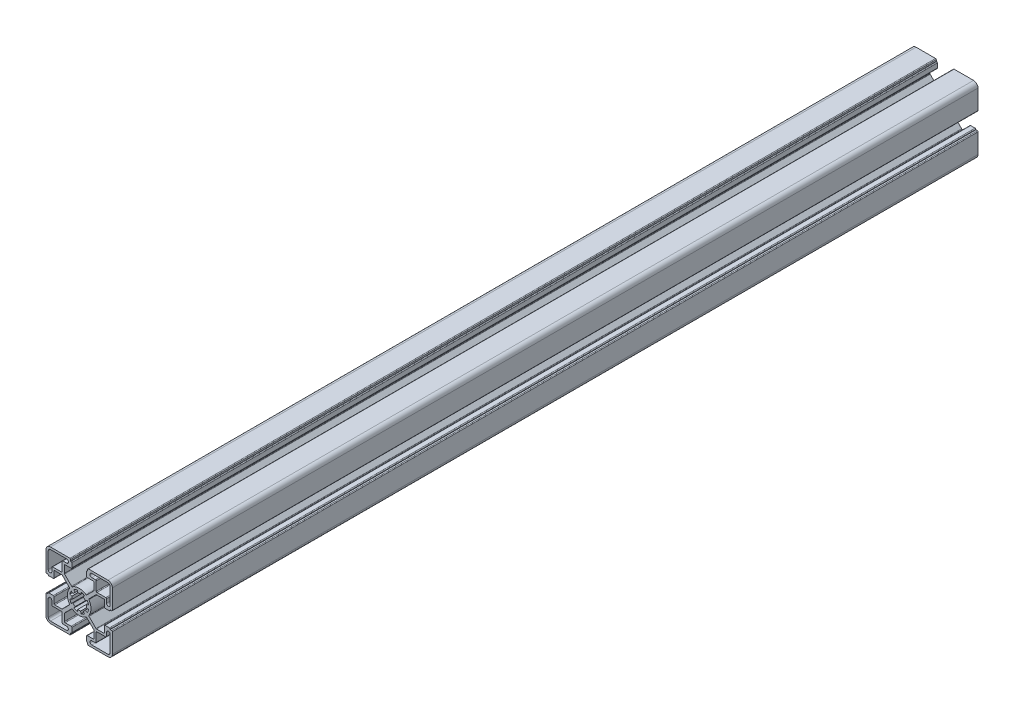
SolidWorks part; units mm, degrees
material "6063-O"
ref_plane "Front Plane" through (0, 0, 0) normal (0, 0, 1) x (1, 0, 0)
ref_plane "Top Plane" through (0, 0, 0) normal (0, 1, 0) x (1, 0, 0)
ref_plane "Right Plane" through (0, 0, 0) normal (1, 0, 0) x (0, 0, -1)
sketch "Sketch1" plane through (0, 0, 0) normal (0, 0, 1) x (1, 0, 0)
  line L0 (0, 22.5) -> (0, -22.5) construction
  line L1 (22.5, 0) -> (-22.5, 0) construction
  line L2 (-5.8, 22.5) -> (5.8, 22.5) construction
  line L3 (-5, 21) -> (5, 21) construction
  line L4 (-10.05, 10.05) -> (10.05, 10.05) construction
  line L5 (0, 0) -> (-10.05, 10.05) construction
  circle A0 centre (0, 0) radius 5 construction
  point P4 (0, 0)
  point P8 (0, 0)
  point P10 (0, 8)
  point P14 (0, 22.5)
  point P17 (0, 21)
  point P19 (0, 10.05)
sketch "Sketch2" plane through (0, 0, 0) normal (1, 0, 0) x (0, 0, -1)
  line L0 (152.4, 0) -> (-152.4, 0) construction
  point P4 (0, 0)
  dimension "D1" = 304.8
sketch "Sketch3" plane through (0, 0, 0) normal (0, 0, 1) x (1, 0, 0)
  line L5 (-21, 8.5375) -> (-21, 19.5)
  line L9 (0, 0) -> (-22.5, 22.5) construction
  line L10 (-11.55, -10.05) -> (-6.3569, -4.8569)
  line L11 (-19.5, 21) -> (-8.5375, 21)
  line L38 (-5.8, 22.5) -> (-5.8, 21)
  line L46 (-5.8, 21) -> (-5, 21)
  line L62 (-5, 21) -> (-5, 17.025)
  line L74 (-5, 17.025) -> (-10.05, 17.025)
  line L76 (-10.05, 17.025) -> (-10.05, 11.55)
  line L77 (-10.05, 11.55) -> (-4.8569, 6.3569)
  line L78 (-18.525, 8.5375) -> (-18.525, 11.55)
  line L79 (-10.05, 17.025) -> (-10.05, 22.5) construction
  line L80 (0, 22.5) -> (0, -22.5) construction
  line L81 (-5.8, 22.5) -> (5.8, 22.5) construction
  line L82 (10.05, 11.55) -> (4.8569, 6.3569)
  line L83 (10.05, 17.025) -> (10.05, 11.55)
  line L84 (5, 17.025) -> (10.05, 17.025)
  line L85 (5, 21) -> (5, 17.025)
  line L86 (5.8, 21) -> (5, 21)
  line L87 (5.8, 22.5) -> (5.8, 21)
  line L88 (-22.5, -5.8) -> (-21, -5.8)
  line L89 (-21, -5.8) -> (-21, -5)
  line L90 (-21, -5) -> (-17.025, -5)
  line L91 (-17.025, -5) -> (-17.025, -10.05)
  line L92 (-17.025, -10.05) -> (-11.55, -10.05)
  line L93 (-11.55, -10.05) -> (-6.3569, -4.8569)
  line L94 (-11.55, 10.05) -> (-6.3569, 4.8569)
  line L95 (-17.025, 10.05) -> (-11.55, 10.05)
  line L96 (-17.025, 5) -> (-17.025, 10.05)
  line L97 (-21, 5) -> (-17.025, 5)
  line L98 (-21, 5.8) -> (-21, 5)
  line L99 (-22.5, 5.8) -> (-21, 5.8)
  line L100 (-22.5, 5.8) -> (-22.5, 19.5)
  line L101 (-19.5, 22.5) -> (-5.8, 22.5)
  line L102 (-18.525, 11.55) -> (-11.55, 11.55)
  line L103 (-8.5375, 18.525) -> (-11.55, 18.525)
  line L104 (-11.55, 18.525) -> (-11.55, 11.55)
  line L108 (5.8, -22.5) -> (5.8, -21)
  line L113 (5.8, -21) -> (5, -21)
  line L117 (5.8, 22.5) -> (19.5, 22.5)
  line L118 (22.5, 19.5) -> (22.5, 5.8)
  line L119 (19.5, -22.5) -> (5.8, -22.5)
  line L120 (0, 0) -> (22.5, 0) construction
  line L121 (-22.5, -19.5) -> (-22.5, -5.8)
  line L136 (5, -21) -> (5, -17.025)
  line L137 (5, -17.025) -> (10.05, -17.025)
  line L138 (10.05, -17.025) -> (10.05, -11.55)
  line L139 (10.05, -11.55) -> (4.8569, -6.3569)
  line L140 (-10.05, -11.55) -> (-4.8569, -6.3569)
  line L141 (-10.05, -17.025) -> (-10.05, -11.55)
  line L142 (-5, -17.025) -> (-10.05, -17.025)
  line L143 (-5, -21) -> (-5, -17.025)
  line L144 (-5.8, -21) -> (-5, -21)
  line L145 (-5.8, -22.5) -> (-5.8, -21)
  line L146 (-5.8, -22.5) -> (-19.5, -22.5)
  line L147 (22.5, 5.8) -> (21, 5.8)
  line L148 (21, 5.8) -> (21, 5)
  line L149 (21, 5) -> (17.025, 5)
  line L150 (17.025, 5) -> (17.025, 10.05)
  line L151 (17.025, 10.05) -> (11.55, 10.05)
  line L152 (11.55, 10.05) -> (6.3569, 4.8569)
  line L153 (11.55, -10.05) -> (6.3569, -4.8569)
  line L154 (17.025, -10.05) -> (11.55, -10.05)
  line L155 (17.025, -5) -> (17.025, -10.05)
  line L156 (21, -5) -> (17.025, -5)
  line L157 (21, -5.8) -> (21, -5)
  line L158 (22.5, -5.8) -> (21, -5.8)
  line L159 (11.55, -10.05) -> (6.3569, -4.8569)
  line L160 (22.5, -5.8) -> (22.5, -19.5)
  line L161 (8.5375, 21) -> (19.5, 21)
  line L162 (21, 19.5) -> (21, 8.5375)
  line L163 (8.5375, 18.525) -> (11.55, 18.525)
  line L164 (11.55, 18.525) -> (11.55, 11.55)
  line L165 (18.525, 8.5375) -> (18.525, 11.55)
  line L166 (18.525, 11.55) -> (11.55, 11.55)
  line L167 (21, -8.5375) -> (21, -19.5)
  line L168 (19.5, -21) -> (8.5375, -21)
  line L169 (18.525, -8.5375) -> (18.525, -11.55)
  line L170 (18.525, -11.55) -> (11.55, -11.55)
  line L171 (8.5375, -18.525) -> (11.55, -18.525)
  line L172 (11.55, -18.525) -> (11.55, -11.55)
  line L173 (-8.5375, -21) -> (-19.5, -21)
  line L174 (-21, -19.5) -> (-21, -8.5375)
  line L175 (-8.5375, -18.525) -> (-11.55, -18.525)
  line L176 (-11.55, -18.525) -> (-11.55, -11.55)
  line L177 (-18.525, -8.5375) -> (-18.525, -11.55)
  line L178 (-18.525, -11.55) -> (-11.55, -11.55)
  line L179 (0, 0) -> (-11.55, 11.55) construction
  line L180 (0, 0) -> (11.55, 11.55) construction
  arc A2 (-21, 19.5) -> (-19.5, 21) centre (-19.5, 19.5) cw
  arc A73 (-4.8569, 6.3569) -> (4.8569, 6.3569) centre (0, 0) cw
  arc A74 (-6.3569, 4.8569) -> (-6.3569, -4.8569) centre (0, 0) ccw
  arc A75 (-19.5, 22.5) -> (-22.5, 19.5) centre (-19.5, 19.5) ccw
  arc A76 (-21, 8.5375) -> (-18.525, 8.5375) centre (-19.7625, 8.5375) ccw
  arc A77 (-8.5375, 21) -> (-8.5375, 18.525) centre (-8.5375, 19.7625) cw
  arc A80 (19.5, 22.5) -> (22.5, 19.5) centre (19.5, 19.5) cw
  arc A81 (22.5, -19.5) -> (19.5, -22.5) centre (19.5, -19.5) cw
  arc A82 (-19.5, -22.5) -> (-22.5, -19.5) centre (-19.5, -19.5) cw
  circle A88 centre (0, 0) radius 5 construction
  circle A89 centre (0, 0) radius 5
  arc A90 (-4.8569, -6.3569) -> (4.8569, -6.3569) centre (0, 0) ccw
  arc A91 (19.5, 21) -> (21, 19.5) centre (19.5, 19.5) cw
  arc A92 (6.3569, 4.8569) -> (6.3569, -4.8569) centre (0, 0) cw
  arc A93 (8.5375, 21) -> (8.5375, 18.525) centre (8.5375, 19.7625) ccw
  arc A94 (21, 8.5375) -> (18.525, 8.5375) centre (19.7625, 8.5375) cw
  arc A95 (21, -19.5) -> (19.5, -21) centre (19.5, -19.5) cw
  arc A96 (21, -8.5375) -> (18.525, -8.5375) centre (19.7625, -8.5375) ccw
  arc A97 (8.5375, -21) -> (8.5375, -18.525) centre (8.5375, -19.7625) cw
  arc A98 (-19.5, -21) -> (-21, -19.5) centre (-19.5, -19.5) cw
  arc A99 (-8.5375, -21) -> (-8.5375, -18.525) centre (-8.5375, -19.7625) ccw
  arc A100 (-21, -8.5375) -> (-18.525, -8.5375) centre (-19.7625, -8.5375) cw
  point P54 (-14.2875, 10.05)
  dimension "D2" = 3
  dimension "D3" = 1.5
  dimension "D4" = 1.5
  dimension "D5" = 1.5
  dimension "D6" = 90
  dimension "D1" = 4
extrude "Boss-Extrude1" add sketch "Sketch3" along normal up to vertex (152.4 mm away) and the other way up to vertex (152.4 mm away) contours A92 L152 L151 L150 L149 L148 L147 L118 A80 L117 L87 L86 L85 L84 L83 L82 A73 L77 L76 L74 L62 L46 L38 L101 A75 L100 L99 L98 L97 L96 L95 L94 A74 L10 L92 L91 L90 L89 L88 L121 A82 L146 L145 L144 L143 L142 L141 L140 A90 L139 L138 up to point (0, 0, 152.4) other way up to point (0, 0, -152.4)
fillet "Fillet1" radius 0.5 58 edges at (5, 21, 0) (5.8, 22.5, 0) (-5.8, 22.5, 0) (-5, 21, 0) (-10.05, 17.025, 0) (-5, 17.025, 0) (5, 17.025, 0) (-22.5, -5.8, 0) (-21, -5, 0) (-17.025, -5, 0) (-17.025, -10.05, 0) (-11.55, -10.05, 0) (-6.3569, -4.8569, 0) (-6.3569, 4.8569, 0) (-11.55, 10.05, 0) (-17.025, 10.05, 0) (-17.025, 5, 0) (-22.5, 5.8, 0) (-21, 5, 0) (-18.525, 11.55, 0) (-11.55, 11.55, 0) (-11.55, 18.525, 0) (4.8569, 6.3569, 0) (-4.8569, 6.3569, 0) (-10.05, 11.55, 0) (10.05, 17.025, 0) (10.05, 11.55, 0) (22.5, -5.8, 0) (21, -5, 0) (17.025, -5, 0) (17.025, -10.05, 0) (6.3569, 4.8569, 0) (11.55, 10.05, 0) (22.5, 5.8, 0) (21, 5, 0) (17.025, 5, 0) (4.8569, -6.3569, 0) (11.55, -11.55, 0) (-11.55, -11.55, 0) (18.525, -11.55, 0) (11.55, -18.525, 0) (10.05, -17.025, 0) (5, -17.025, 0) (5, -21, 0) (5.8, -22.5, 0) (-5.8, -22.5, 0) (-5, -21, 0) (-5, -17.025, 0) (-10.05, -17.025, 0) (-11.55, -18.525, 0) (11.55, 18.525, 0) (18.525, 11.55, 0) (11.55, 11.55, 0) (11.55, -10.05, 0) (6.3569, -4.8569, 0) (-4.8569, -6.3569, 0) (10.05, -11.55, 0) (-10.05, -11.55, 0)
sketch "Sketch4" plane through (0, 0, 152.4) normal (0, 0, 1) x (1, 0, 0)
  line L0 (-1.2681, 6.3751) -> (-0.9755, 4.9039)
  line L1 (0, 0) -> (0, 8) construction
  line L2 (-3.6112, 5.4046) -> (-2.7779, 4.1573)
  line L3 (1.2681, 6.3751) -> (0.9755, 4.9039)
  line L4 (3.6112, 5.4046) -> (2.7779, 4.1573)
  line L5 (5.4046, 3.6112) -> (4.1573, 2.7779)
  line L6 (6.3751, 1.2681) -> (4.9039, 0.9755)
  line L7 (6.3751, -1.2681) -> (4.9039, -0.9755)
  line L8 (5.4046, -3.6112) -> (4.1573, -2.7779)
  line L9 (3.6112, -5.4046) -> (2.7779, -4.1573)
  line L10 (1.2681, -6.3751) -> (0.9755, -4.9039)
  line L11 (-1.2681, -6.3751) -> (-0.9755, -4.9039)
  line L12 (-3.6112, -5.4046) -> (-2.7779, -4.1573)
  line L13 (-5.4046, -3.6112) -> (-4.1573, -2.7779)
  line L14 (-6.3751, -1.2681) -> (-4.9039, -0.9755)
  line L15 (-6.3751, 1.2681) -> (-4.9039, 0.9755)
  line L16 (-5.4046, 3.6112) -> (-4.1573, 2.7779)
  line L17 (0, 0) -> (-0.9755, 4.9039) construction
  line L18 (0, 0) -> (2.7779, 4.1573) construction
  arc A0 (-1.2681, 6.3751) -> (-3.6112, 5.4046) centre (0, 0) ccw
  circle A1 centre (0, 0) radius 5 construction
  arc A2 (-0.9755, 4.9039) -> (-2.7779, 4.1573) centre (0, 0) ccw
  arc A4 (2.7779, 4.1573) -> (0.9755, 4.9039) centre (0, 0) ccw
  arc A5 (3.6112, 5.4046) -> (1.2681, 6.3751) centre (0, 0) ccw
  arc A6 (4.9039, 0.9755) -> (4.1573, 2.7779) centre (0, 0) ccw
  arc A7 (6.3751, 1.2681) -> (5.4046, 3.6112) centre (0, 0) ccw
  arc A8 (4.1573, -2.7779) -> (4.9039, -0.9755) centre (0, 0) ccw
  arc A9 (5.4046, -3.6112) -> (6.3751, -1.2681) centre (0, 0) ccw
  arc A10 (0.9755, -4.9039) -> (2.7779, -4.1573) centre (0, 0) ccw
  arc A11 (1.2681, -6.3751) -> (3.6112, -5.4046) centre (0, 0) ccw
  arc A12 (-2.7779, -4.1573) -> (-0.9755, -4.9039) centre (0, 0) ccw
  arc A13 (-3.6112, -5.4046) -> (-1.2681, -6.3751) centre (0, 0) ccw
  arc A14 (-4.9039, -0.9755) -> (-4.1573, -2.7779) centre (0, 0) ccw
  arc A15 (-6.3751, -1.2681) -> (-5.4046, -3.6112) centre (0, 0) ccw
  arc A16 (-4.1573, 2.7779) -> (-4.9039, 0.9755) centre (0, 0) ccw
  arc A17 (-5.4046, 3.6112) -> (-6.3751, 1.2681) centre (0, 0) ccw
  dimension "D1" = 1.5
  dimension "D2" = 22.5
  dimension "D5" = 45
  dimension "D4" = 8
extrude "Cut-Extrude1" cut sketch "Sketch4" against normal through all
sketch "Sketch6" plane through (0, 0, 152.4) normal (0, 0, 1) x (1, 0, 0)
  line L6 (-11.55, -18.025) -> (-11.55, -12.05)
  line L7 (-8.5375, -18.525) -> (-11.05, -18.525)
  line L8 (-19.5, -21) -> (-8.5375, -21)
  line L9 (-21, -8.5375) -> (-21, -19.5)
  line L10 (-18.525, -11.55) -> (-18.525, -8.5375)
  line L11 (-12.05, -11.55) -> (-18.525, -11.55)
  line L12 (-11.55, -18.025) -> (-11.55, -12.05)
  line L13 (-8.5375, -18.525) -> (-11.05, -18.525)
  line L14 (-19.5, -21) -> (-8.5375, -21)
  line L15 (-21, -8.5375) -> (-21, -19.5)
  line L16 (-0.9755, 4.9039) -> (-1.2681, 6.3751)
  line L17 (1.2681, 6.3751) -> (0.9755, 4.9039)
  line L18 (2.7779, 4.1573) -> (3.6112, 5.4046)
  line L19 (5.4046, 3.6112) -> (4.1573, 2.7779)
  line L20 (4.9039, 0.9755) -> (6.3751, 1.2681)
  line L21 (6.3751, -1.2681) -> (4.9039, -0.9755)
  line L22 (4.1573, -2.7779) -> (5.4046, -3.6112)
  line L23 (3.6112, -5.4046) -> (2.7779, -4.1573)
  line L24 (0.9755, -4.9039) -> (1.2681, -6.3751)
  line L25 (-1.2681, -6.3751) -> (-0.9755, -4.9039)
  line L26 (-2.7779, -4.1573) -> (-3.6112, -5.4046)
  line L27 (-5.4046, -3.6112) -> (-4.1573, -2.7779)
  line L28 (-4.9039, -0.9755) -> (-6.3751, -1.2681)
  line L29 (-6.3751, 1.2681) -> (-4.9039, 0.9755)
  line L30 (-4.1573, 2.7779) -> (-5.4046, 3.6112)
  line L31 (-3.6112, 5.4046) -> (-2.7779, 4.1573)
  line L32 (-0.9755, 4.9039) -> (-1.2681, 6.3751)
  line L33 (1.2681, 6.3751) -> (0.9755, 4.9039)
  line L34 (2.7779, 4.1573) -> (3.6112, 5.4046)
  line L35 (5.4046, 3.6112) -> (4.1573, 2.7779)
  line L36 (4.9039, 0.9755) -> (6.3751, 1.2681)
  line L37 (6.3751, -1.2681) -> (4.9039, -0.9755)
  line L38 (4.1573, -2.7779) -> (5.4046, -3.6112)
  line L39 (3.6112, -5.4046) -> (2.7779, -4.1573)
  line L40 (0.9755, -4.9039) -> (1.2681, -6.3751)
  line L41 (-1.2681, -6.3751) -> (-0.9755, -4.9039)
  line L42 (-2.7779, -4.1573) -> (-3.6112, -5.4046)
  line L43 (-5.4046, -3.6112) -> (-4.1573, -2.7779)
  line L44 (-4.9039, -0.9755) -> (-6.3751, -1.2681)
  line L45 (-6.3751, 1.2681) -> (-4.9039, 0.9755)
  line L46 (-4.1573, 2.7779) -> (-5.4046, 3.6112)
  line L47 (-3.6112, 5.4046) -> (-2.7779, 4.1573)
  line L48 (-18.525, -11.55) -> (-18.525, -8.5375)
  line L49 (-12.05, -11.55) -> (-18.525, -11.55)
  line L50 (18.025, -11.55) -> (12.05, -11.55)
  line L51 (18.525, -8.5375) -> (18.525, -11.05)
  line L52 (21, -19.5) -> (21, -8.5375)
  line L53 (8.5375, -21) -> (19.5, -21)
  line L54 (11.05, -18.525) -> (8.5375, -18.525)
  line L55 (11.55, -12.05) -> (11.55, -18.025)
  line L56 (22.5, -19.5) -> (22.5, -6.3)
  line L57 (22, -5.8) -> (21, -5.8)
  line L58 (21, -5.8) -> (21, -5.5)
  line L59 (20.5, -5) -> (17.525, -5)
  line L60 (17.025, -5.5) -> (17.025, -9.55)
  line L61 (16.525, -10.05) -> (11.7571, -10.05)
  line L62 (11.4036, -9.9036) -> (6.6582, -5.1582)
  line L63 (6.6582, 5.1582) -> (11.4036, 9.9036)
  line L64 (11.7571, 10.05) -> (17.025, 10.05)
  line L65 (17.025, 10.05) -> (17.025, 5.5)
  line L66 (17.525, 5) -> (20.5, 5)
  line L67 (21, 5.5) -> (21, 5.8)
  line L68 (21, 5.8) -> (22, 5.8)
  line L69 (22.5, 6.3) -> (22.5, 19.5)
  line L70 (19.5, 22.5) -> (6.3, 22.5)
  line L71 (5.8, 22) -> (5.8, 21)
  line L72 (5.8, 21) -> (5.5, 21)
  line L73 (5, 20.5) -> (5, 17.525)
  line L74 (5.5, 17.025) -> (9.55, 17.025)
  line L75 (10.05, 16.525) -> (10.05, 11.7571)
  line L76 (9.9036, 11.4036) -> (5.1582, 6.6582)
  line L77 (-5.1582, 6.6582) -> (-9.9036, 11.4036)
  line L78 (-10.05, 11.7571) -> (-10.05, 16.525)
  line L79 (-9.55, 17.025) -> (-5.5, 17.025)
  line L80 (-5, 17.525) -> (-5, 20.5)
  line L81 (-5.5, 21) -> (-5.8, 21)
  line L82 (-5.8, 21) -> (-5.8, 22)
  line L83 (-6.3, 22.5) -> (-19.5, 22.5)
  line L84 (-22.5, 19.5) -> (-22.5, 6.3)
  line L85 (-22, 5.8) -> (-21, 5.8)
  line L86 (-21, 5.8) -> (-21, 5.5)
  line L87 (-20.5, 5) -> (-17.525, 5)
  line L88 (-17.025, 5.5) -> (-17.025, 9.55)
  line L89 (-16.525, 10.05) -> (-11.7571, 10.05)
  line L90 (-11.4036, 9.9036) -> (-6.6582, 5.1582)
  line L91 (-6.6582, -5.1582) -> (-11.4036, -9.9036)
  line L92 (-11.7571, -10.05) -> (-16.525, -10.05)
  line L93 (-17.025, -9.55) -> (-17.025, -5.5)
  line L94 (-17.525, -5) -> (-20.5, -5)
  line L95 (-21, -5.5) -> (-21, -5.8)
  line L96 (-21, -5.8) -> (-22, -5.8)
  line L97 (-22.5, -6.3) -> (-22.5, -19.5)
  line L98 (-19.5, -22.5) -> (-6.3, -22.5)
  line L99 (-5.8, -22) -> (-5.8, -21)
  line L100 (-5.8, -21) -> (-5.5, -21)
  line L101 (-5, -20.5) -> (-5, -17.525)
  line L102 (-5.5, -17.025) -> (-9.55, -17.025)
  line L103 (-10.05, -16.525) -> (-10.05, -11.7571)
  line L104 (-9.9036, -11.4036) -> (-5.1582, -6.6582)
  line L105 (5.1582, -6.6582) -> (9.9036, -11.4036)
  line L106 (10.05, -11.7571) -> (10.05, -16.525)
  line L107 (9.55, -17.025) -> (5.5, -17.025)
  line L108 (5, -17.525) -> (5, -20.5)
  line L109 (5.5, -21) -> (5.8, -21)
  line L110 (5.8, -21) -> (5.8, -22)
  line L111 (6.3, -22.5) -> (19.5, -22.5)
  line L112 (22.5, -19.5) -> (22.5, -6.3)
  line L113 (22, -5.8) -> (21, -5.8)
  line L114 (21, -5.8) -> (21, -5.5)
  line L115 (20.5, -5) -> (17.525, -5)
  line L116 (17.025, -5.5) -> (17.025, -9.55)
  line L117 (16.525, -10.05) -> (11.7571, -10.05)
  line L118 (11.4036, -9.9036) -> (6.6582, -5.1582)
  line L119 (6.6582, 5.1582) -> (11.4036, 9.9036)
  line L120 (11.7571, 10.05) -> (17.025, 10.05)
  line L121 (17.025, 10.05) -> (17.025, 5.5)
  line L122 (17.525, 5) -> (20.5, 5)
  line L123 (21, 5.5) -> (21, 5.8)
  line L124 (21, 5.8) -> (22, 5.8)
  line L125 (22.5, 6.3) -> (22.5, 19.5)
  line L126 (19.5, 22.5) -> (6.3, 22.5)
  line L127 (5.8, 22) -> (5.8, 21)
  line L128 (5.8, 21) -> (5.5, 21)
  line L129 (5, 20.5) -> (5, 17.525)
  line L130 (5.5, 17.025) -> (9.55, 17.025)
  line L131 (10.05, 16.525) -> (10.05, 11.7571)
  line L132 (9.9036, 11.4036) -> (5.1582, 6.6582)
  line L133 (-5.1582, 6.6582) -> (-9.9036, 11.4036)
  line L134 (-10.05, 11.7571) -> (-10.05, 16.525)
  line L135 (-9.55, 17.025) -> (-5.5, 17.025)
  line L136 (-5, 17.525) -> (-5, 20.5)
  line L137 (-5.5, 21) -> (-5.8, 21)
  line L138 (-5.8, 21) -> (-5.8, 22)
  line L139 (-6.3, 22.5) -> (-19.5, 22.5)
  line L140 (-22.5, 19.5) -> (-22.5, 6.3)
  line L141 (-22, 5.8) -> (-21, 5.8)
  line L142 (-21, 5.8) -> (-21, 5.5)
  line L143 (-20.5, 5) -> (-17.525, 5)
  line L144 (-17.025, 5.5) -> (-17.025, 9.55)
  line L145 (-16.525, 10.05) -> (-11.7571, 10.05)
  line L146 (-11.4036, 9.9036) -> (-6.6582, 5.1582)
  line L147 (-6.6582, -5.1582) -> (-11.4036, -9.9036)
  line L148 (-11.7571, -10.05) -> (-16.525, -10.05)
  line L149 (-17.025, -9.55) -> (-17.025, -5.5)
  line L150 (-17.525, -5) -> (-20.5, -5)
  line L151 (-21, -5.5) -> (-21, -5.8)
  line L152 (-21, -5.8) -> (-22, -5.8)
  line L153 (-22.5, -6.3) -> (-22.5, -19.5)
  line L154 (-19.5, -22.5) -> (-6.3, -22.5)
  line L155 (-5.8, -22) -> (-5.8, -21)
  line L156 (-5.8, -21) -> (-5.5, -21)
  line L157 (-5, -20.5) -> (-5, -17.525)
  line L158 (-5.5, -17.025) -> (-9.55, -17.025)
  line L159 (-10.05, -16.525) -> (-10.05, -11.7571)
  line L160 (-9.9036, -11.4036) -> (-5.1582, -6.6582)
  line L161 (5.1582, -6.6582) -> (9.9036, -11.4036)
  line L162 (10.05, -11.7571) -> (10.05, -16.525)
  line L163 (9.55, -17.025) -> (5.5, -17.025)
  line L164 (5, -17.525) -> (5, -20.5)
  line L165 (5.5, -21) -> (5.8, -21)
  line L166 (5.8, -21) -> (5.8, -22)
  line L167 (6.3, -22.5) -> (19.5, -22.5)
  line L168 (18.025, -11.55) -> (12.05, -11.55)
  line L169 (18.525, -8.5375) -> (18.525, -11.05)
  line L170 (21, -19.5) -> (21, -8.5375)
  line L171 (8.5375, -21) -> (19.5, -21)
  line L172 (11.05, -18.525) -> (8.5375, -18.525)
  line L173 (11.55, -12.05) -> (11.55, -18.025)
  line L174 (11.55, 18.025) -> (11.55, 12.05)
  line L175 (8.5375, 18.525) -> (11.05, 18.525)
  line L176 (19.5, 21) -> (8.5375, 21)
  line L177 (21, 8.5375) -> (21, 19.5)
  line L178 (18.525, 11.05) -> (18.525, 8.5375)
  line L179 (12.05, 11.55) -> (18.025, 11.55)
  line L180 (11.55, 18.025) -> (11.55, 12.05)
  line L181 (8.5375, 18.525) -> (11.05, 18.525)
  line L182 (19.5, 21) -> (8.5375, 21)
  line L183 (21, 8.5375) -> (21, 19.5)
  line L184 (18.525, 11.05) -> (18.525, 8.5375)
  line L185 (12.05, 11.55) -> (18.025, 11.55)
  line L186 (-18.025, 11.55) -> (-12.05, 11.55)
  line L187 (-18.525, 8.5375) -> (-18.525, 11.05)
  line L188 (-21, 19.5) -> (-21, 8.5375)
  line L189 (-8.5375, 21) -> (-19.5, 21)
  line L190 (-11.05, 18.525) -> (-8.5375, 18.525)
  line L191 (-11.55, 12.05) -> (-11.55, 18.025)
  line L192 (-18.025, 11.55) -> (-12.05, 11.55)
  line L193 (-18.525, 8.5375) -> (-18.525, 11.05)
  line L194 (-21, 19.5) -> (-21, 8.5375)
  line L195 (-8.5375, 21) -> (-19.5, 21)
  line L196 (-11.05, 18.525) -> (-8.5375, 18.525)
  line L197 (-11.55, 12.05) -> (-11.55, 18.025)
  arc A5 (-11.55, -18.025) -> (-11.05, -18.525) centre (-11.05, -18.025) ccw
  arc A6 (-8.5375, -21) -> (-8.5375, -18.525) centre (-8.5375, -19.7625) ccw
  arc A7 (-21, -19.5) -> (-19.5, -21) centre (-19.5, -19.5) ccw
  arc A8 (-18.525, -8.5375) -> (-21, -8.5375) centre (-19.7625, -8.5375) ccw
  arc A9 (-11.55, -12.05) -> (-12.05, -11.55) centre (-12.05, -12.05) ccw
  arc A10 (-11.55, -18.025) -> (-11.05, -18.525) centre (-11.05, -18.025) ccw
  arc A11 (-8.5375, -21) -> (-8.5375, -18.525) centre (-8.5375, -19.7625) ccw
  arc A12 (-21, -19.5) -> (-19.5, -21) centre (-19.5, -19.5) ccw
  arc A13 (-18.525, -8.5375) -> (-21, -8.5375) centre (-19.7625, -8.5375) ccw
  arc A14 (-11.55, -12.05) -> (-12.05, -11.55) centre (-12.05, -12.05) ccw
  arc A16 (0.9755, 4.9039) -> (-0.9755, 4.9039) centre (0, 0) ccw
  arc A17 (3.6112, 5.4046) -> (1.2681, 6.3751) centre (0, 0) ccw
  arc A18 (4.1573, 2.7779) -> (2.7779, 4.1573) centre (0, 0) ccw
  arc A19 (6.3751, 1.2681) -> (5.4046, 3.6112) centre (0, 0) ccw
  arc A20 (4.9039, -0.9755) -> (4.9039, 0.9755) centre (0, 0) ccw
  arc A21 (5.4046, -3.6112) -> (6.3751, -1.2681) centre (0, 0) ccw
  arc A22 (2.7779, -4.1573) -> (4.1573, -2.7779) centre (0, 0) ccw
  arc A23 (1.2681, -6.3751) -> (3.6112, -5.4046) centre (0, 0) ccw
  arc A24 (-0.9755, -4.9039) -> (0.9755, -4.9039) centre (0, 0) ccw
  arc A25 (-3.6112, -5.4046) -> (-1.2681, -6.3751) centre (0, 0) ccw
  arc A26 (-4.1573, -2.7779) -> (-2.7779, -4.1573) centre (0, 0) ccw
  arc A27 (-6.3751, -1.2681) -> (-5.4046, -3.6112) centre (0, 0) ccw
  arc A28 (-4.9039, 0.9755) -> (-4.9039, -0.9755) centre (0, 0) ccw
  arc A29 (-5.4046, 3.6112) -> (-6.3751, 1.2681) centre (0, 0) ccw
  arc A30 (-2.7779, 4.1573) -> (-4.1573, 2.7779) centre (0, 0) ccw
  arc A31 (-1.2681, 6.3751) -> (-3.6112, 5.4046) centre (0, 0) ccw
  arc A32 (0.9755, 4.9039) -> (-0.9755, 4.9039) centre (0, 0) ccw
  arc A33 (3.6112, 5.4046) -> (1.2681, 6.3751) centre (0, 0) ccw
  arc A34 (4.1573, 2.7779) -> (2.7779, 4.1573) centre (0, 0) ccw
  arc A35 (6.3751, 1.2681) -> (5.4046, 3.6112) centre (0, 0) ccw
  arc A36 (4.9039, -0.9755) -> (4.9039, 0.9755) centre (0, 0) ccw
  arc A37 (5.4046, -3.6112) -> (6.3751, -1.2681) centre (0, 0) ccw
  arc A38 (2.7779, -4.1573) -> (4.1573, -2.7779) centre (0, 0) ccw
  arc A39 (1.2681, -6.3751) -> (3.6112, -5.4046) centre (0, 0) ccw
  arc A40 (-0.9755, -4.9039) -> (0.9755, -4.9039) centre (0, 0) ccw
  arc A41 (-3.6112, -5.4046) -> (-1.2681, -6.3751) centre (0, 0) ccw
  arc A42 (-4.1573, -2.7779) -> (-2.7779, -4.1573) centre (0, 0) ccw
  arc A43 (-6.3751, -1.2681) -> (-5.4046, -3.6112) centre (0, 0) ccw
  arc A44 (-4.9039, 0.9755) -> (-4.9039, -0.9755) centre (0, 0) ccw
  arc A45 (-5.4046, 3.6112) -> (-6.3751, 1.2681) centre (0, 0) ccw
  arc A46 (-2.7779, 4.1573) -> (-4.1573, 2.7779) centre (0, 0) ccw
  arc A47 (-1.2681, 6.3751) -> (-3.6112, 5.4046) centre (0, 0) ccw
  arc A48 (18.025, -11.55) -> (18.525, -11.05) centre (18.025, -11.05) ccw
  arc A49 (21, -8.5375) -> (18.525, -8.5375) centre (19.7625, -8.5375) ccw
  arc A50 (19.5, -21) -> (21, -19.5) centre (19.5, -19.5) ccw
  arc A51 (8.5375, -18.525) -> (8.5375, -21) centre (8.5375, -19.7625) ccw
  arc A52 (11.05, -18.525) -> (11.55, -18.025) centre (11.05, -18.025) ccw
  arc A53 (12.05, -11.55) -> (11.55, -12.05) centre (12.05, -12.05) ccw
  arc A54 (18.025, -11.55) -> (18.525, -11.05) centre (18.025, -11.05) ccw
  arc A55 (22.5, -6.3) -> (22, -5.8) centre (22, -6.3) ccw
  arc A56 (21, -5.5) -> (20.5, -5) centre (20.5, -5.5) ccw
  arc A57 (17.525, -5) -> (17.025, -5.5) centre (17.525, -5.5) ccw
  arc A58 (16.525, -10.05) -> (17.025, -9.55) centre (16.525, -9.55) ccw
  arc A59 (11.4036, -9.9036) -> (11.7571, -10.05) centre (11.7571, -9.55) ccw
  arc A60 (6.5993, -4.522) -> (6.6582, -5.1582) centre (7.0118, -4.8047) ccw
  arc A61 (6.5993, -4.522) -> (6.5993, 4.522) centre (0, 0) ccw
  arc A62 (6.6582, 5.1582) -> (6.5993, 4.522) centre (7.0118, 4.8047) ccw
  arc A63 (11.7571, 10.05) -> (11.4036, 9.9036) centre (11.7571, 9.55) ccw
  arc A64 (17.025, 5.5) -> (17.525, 5) centre (17.525, 5.5) ccw
  arc A65 (20.5, 5) -> (21, 5.5) centre (20.5, 5.5) ccw
  arc A66 (22, 5.8) -> (22.5, 6.3) centre (22, 6.3) ccw
  arc A67 (22.5, 19.5) -> (19.5, 22.5) centre (19.5, 19.5) ccw
  arc A68 (6.3, 22.5) -> (5.8, 22) centre (6.3, 22) ccw
  arc A69 (5.5, 21) -> (5, 20.5) centre (5.5, 20.5) ccw
  arc A70 (5, 17.525) -> (5.5, 17.025) centre (5.5, 17.525) ccw
  arc A71 (10.05, 16.525) -> (9.55, 17.025) centre (9.55, 16.525) ccw
  arc A72 (9.9036, 11.4036) -> (10.05, 11.7571) centre (9.55, 11.7571) ccw
  arc A73 (4.522, 6.5993) -> (5.1582, 6.6582) centre (4.8047, 7.0118) ccw
  arc A74 (4.522, 6.5993) -> (-4.522, 6.5993) centre (0, 0) ccw
  arc A75 (-5.1582, 6.6582) -> (-4.522, 6.5993) centre (-4.8047, 7.0118) ccw
  arc A76 (-10.05, 11.7571) -> (-9.9036, 11.4036) centre (-9.55, 11.7571) ccw
  arc A77 (-9.55, 17.025) -> (-10.05, 16.525) centre (-9.55, 16.525) ccw
  arc A78 (-5.5, 17.025) -> (-5, 17.525) centre (-5.5, 17.525) ccw
  arc A79 (-5, 20.5) -> (-5.5, 21) centre (-5.5, 20.5) ccw
  arc A80 (-5.8, 22) -> (-6.3, 22.5) centre (-6.3, 22) ccw
  arc A81 (-19.5, 22.5) -> (-22.5, 19.5) centre (-19.5, 19.5) ccw
  arc A82 (-22.5, 6.3) -> (-22, 5.8) centre (-22, 6.3) ccw
  arc A83 (-21, 5.5) -> (-20.5, 5) centre (-20.5, 5.5) ccw
  arc A84 (-17.525, 5) -> (-17.025, 5.5) centre (-17.525, 5.5) ccw
  arc A85 (-16.525, 10.05) -> (-17.025, 9.55) centre (-16.525, 9.55) ccw
  arc A86 (-11.4036, 9.9036) -> (-11.7571, 10.05) centre (-11.7571, 9.55) ccw
  arc A87 (-6.5993, 4.522) -> (-6.6582, 5.1582) centre (-7.0118, 4.8047) ccw
  arc A88 (-6.5993, 4.522) -> (-6.5993, -4.522) centre (0, 0) ccw
  arc A89 (-6.6582, -5.1582) -> (-6.5993, -4.522) centre (-7.0118, -4.8047) ccw
  arc A90 (-11.7571, -10.05) -> (-11.4036, -9.9036) centre (-11.7571, -9.55) ccw
  arc A91 (-17.025, -9.55) -> (-16.525, -10.05) centre (-16.525, -9.55) ccw
  arc A92 (-17.025, -5.5) -> (-17.525, -5) centre (-17.525, -5.5) ccw
  arc A93 (-20.5, -5) -> (-21, -5.5) centre (-20.5, -5.5) ccw
  arc A94 (-22, -5.8) -> (-22.5, -6.3) centre (-22, -6.3) ccw
  arc A95 (-22.5, -19.5) -> (-19.5, -22.5) centre (-19.5, -19.5) ccw
  arc A96 (-6.3, -22.5) -> (-5.8, -22) centre (-6.3, -22) ccw
  arc A97 (-5.5, -21) -> (-5, -20.5) centre (-5.5, -20.5) ccw
  arc A98 (-5, -17.525) -> (-5.5, -17.025) centre (-5.5, -17.525) ccw
  arc A99 (-10.05, -16.525) -> (-9.55, -17.025) centre (-9.55, -16.525) ccw
  arc A100 (-9.9036, -11.4036) -> (-10.05, -11.7571) centre (-9.55, -11.7571) ccw
  arc A101 (-4.522, -6.5993) -> (-5.1582, -6.6582) centre (-4.8047, -7.0118) ccw
  arc A102 (-4.522, -6.5993) -> (4.522, -6.5993) centre (0, 0) ccw
  arc A103 (5.1582, -6.6582) -> (4.522, -6.5993) centre (4.8047, -7.0118) ccw
  arc A104 (10.05, -11.7571) -> (9.9036, -11.4036) centre (9.55, -11.7571) ccw
  arc A105 (9.55, -17.025) -> (10.05, -16.525) centre (9.55, -16.525) ccw
  arc A106 (5.5, -17.025) -> (5, -17.525) centre (5.5, -17.525) ccw
  arc A107 (5, -20.5) -> (5.5, -21) centre (5.5, -20.5) ccw
  arc A108 (5.8, -22) -> (6.3, -22.5) centre (6.3, -22) ccw
  arc A109 (19.5, -22.5) -> (22.5, -19.5) centre (19.5, -19.5) ccw
  arc A110 (22.5, -6.3) -> (22, -5.8) centre (22, -6.3) ccw
  arc A111 (21, -5.5) -> (20.5, -5) centre (20.5, -5.5) ccw
  arc A112 (17.525, -5) -> (17.025, -5.5) centre (17.525, -5.5) ccw
  arc A113 (16.525, -10.05) -> (17.025, -9.55) centre (16.525, -9.55) ccw
  arc A114 (11.4036, -9.9036) -> (11.7571, -10.05) centre (11.7571, -9.55) ccw
  arc A115 (6.5993, -4.522) -> (6.6582, -5.1582) centre (7.0118, -4.8047) ccw
  arc A116 (6.5993, -4.522) -> (6.5993, 4.522) centre (0, 0) ccw
  arc A117 (6.6582, 5.1582) -> (6.5993, 4.522) centre (7.0118, 4.8047) ccw
  arc A118 (11.7571, 10.05) -> (11.4036, 9.9036) centre (11.7571, 9.55) ccw
  arc A119 (17.025, 5.5) -> (17.525, 5) centre (17.525, 5.5) ccw
  arc A120 (20.5, 5) -> (21, 5.5) centre (20.5, 5.5) ccw
  arc A121 (22, 5.8) -> (22.5, 6.3) centre (22, 6.3) ccw
  arc A122 (22.5, 19.5) -> (19.5, 22.5) centre (19.5, 19.5) ccw
  arc A123 (6.3, 22.5) -> (5.8, 22) centre (6.3, 22) ccw
  arc A124 (5.5, 21) -> (5, 20.5) centre (5.5, 20.5) ccw
  arc A125 (5, 17.525) -> (5.5, 17.025) centre (5.5, 17.525) ccw
  arc A126 (10.05, 16.525) -> (9.55, 17.025) centre (9.55, 16.525) ccw
  arc A127 (9.9036, 11.4036) -> (10.05, 11.7571) centre (9.55, 11.7571) ccw
  arc A128 (4.522, 6.5993) -> (5.1582, 6.6582) centre (4.8047, 7.0118) ccw
  arc A129 (4.522, 6.5993) -> (-4.522, 6.5993) centre (0, 0) ccw
  arc A130 (-5.1582, 6.6582) -> (-4.522, 6.5993) centre (-4.8047, 7.0118) ccw
  arc A131 (-10.05, 11.7571) -> (-9.9036, 11.4036) centre (-9.55, 11.7571) ccw
  arc A132 (-9.55, 17.025) -> (-10.05, 16.525) centre (-9.55, 16.525) ccw
  arc A133 (-5.5, 17.025) -> (-5, 17.525) centre (-5.5, 17.525) ccw
  arc A134 (-5, 20.5) -> (-5.5, 21) centre (-5.5, 20.5) ccw
  arc A135 (-5.8, 22) -> (-6.3, 22.5) centre (-6.3, 22) ccw
  arc A136 (-19.5, 22.5) -> (-22.5, 19.5) centre (-19.5, 19.5) ccw
  arc A137 (-22.5, 6.3) -> (-22, 5.8) centre (-22, 6.3) ccw
  arc A138 (-21, 5.5) -> (-20.5, 5) centre (-20.5, 5.5) ccw
  arc A139 (-17.525, 5) -> (-17.025, 5.5) centre (-17.525, 5.5) ccw
  arc A140 (-16.525, 10.05) -> (-17.025, 9.55) centre (-16.525, 9.55) ccw
  arc A141 (-11.4036, 9.9036) -> (-11.7571, 10.05) centre (-11.7571, 9.55) ccw
  arc A142 (-6.5993, 4.522) -> (-6.6582, 5.1582) centre (-7.0118, 4.8047) ccw
  arc A143 (-6.5993, 4.522) -> (-6.5993, -4.522) centre (0, 0) ccw
  arc A144 (-6.6582, -5.1582) -> (-6.5993, -4.522) centre (-7.0118, -4.8047) ccw
  arc A145 (-11.7571, -10.05) -> (-11.4036, -9.9036) centre (-11.7571, -9.55) ccw
  arc A146 (-17.025, -9.55) -> (-16.525, -10.05) centre (-16.525, -9.55) ccw
  arc A147 (-17.025, -5.5) -> (-17.525, -5) centre (-17.525, -5.5) ccw
  arc A148 (-20.5, -5) -> (-21, -5.5) centre (-20.5, -5.5) ccw
  arc A149 (-22, -5.8) -> (-22.5, -6.3) centre (-22, -6.3) ccw
  arc A150 (-22.5, -19.5) -> (-19.5, -22.5) centre (-19.5, -19.5) ccw
  arc A151 (-6.3, -22.5) -> (-5.8, -22) centre (-6.3, -22) ccw
  arc A152 (-5.5, -21) -> (-5, -20.5) centre (-5.5, -20.5) ccw
  arc A153 (-5, -17.525) -> (-5.5, -17.025) centre (-5.5, -17.525) ccw
  arc A154 (-10.05, -16.525) -> (-9.55, -17.025) centre (-9.55, -16.525) ccw
  arc A155 (-9.9036, -11.4036) -> (-10.05, -11.7571) centre (-9.55, -11.7571) ccw
  arc A156 (-4.522, -6.5993) -> (-5.1582, -6.6582) centre (-4.8047, -7.0118) ccw
  arc A157 (-4.522, -6.5993) -> (4.522, -6.5993) centre (0, 0) ccw
  arc A158 (5.1582, -6.6582) -> (4.522, -6.5993) centre (4.8047, -7.0118) ccw
  arc A159 (10.05, -11.7571) -> (9.9036, -11.4036) centre (9.55, -11.7571) ccw
  arc A160 (9.55, -17.025) -> (10.05, -16.525) centre (9.55, -16.525) ccw
  arc A161 (5.5, -17.025) -> (5, -17.525) centre (5.5, -17.525) ccw
  arc A162 (5, -20.5) -> (5.5, -21) centre (5.5, -20.5) ccw
  arc A163 (5.8, -22) -> (6.3, -22.5) centre (6.3, -22) ccw
  arc A164 (19.5, -22.5) -> (22.5, -19.5) centre (19.5, -19.5) ccw
  arc A165 (21, -8.5375) -> (18.525, -8.5375) centre (19.7625, -8.5375) ccw
  arc A166 (19.5, -21) -> (21, -19.5) centre (19.5, -19.5) ccw
  arc A167 (8.5375, -18.525) -> (8.5375, -21) centre (8.5375, -19.7625) ccw
  arc A168 (11.05, -18.525) -> (11.55, -18.025) centre (11.05, -18.025) ccw
  arc A169 (12.05, -11.55) -> (11.55, -12.05) centre (12.05, -12.05) ccw
  arc A170 (11.55, 18.025) -> (11.05, 18.525) centre (11.05, 18.025) ccw
  arc A171 (8.5375, 21) -> (8.5375, 18.525) centre (8.5375, 19.7625) ccw
  arc A172 (21, 19.5) -> (19.5, 21) centre (19.5, 19.5) ccw
  arc A173 (18.525, 8.5375) -> (21, 8.5375) centre (19.7625, 8.5375) ccw
  arc A174 (18.525, 11.05) -> (18.025, 11.55) centre (18.025, 11.05) ccw
  arc A175 (11.55, 12.05) -> (12.05, 11.55) centre (12.05, 12.05) ccw
  arc A176 (11.55, 18.025) -> (11.05, 18.525) centre (11.05, 18.025) ccw
  arc A177 (8.5375, 21) -> (8.5375, 18.525) centre (8.5375, 19.7625) ccw
  arc A178 (21, 19.5) -> (19.5, 21) centre (19.5, 19.5) ccw
  arc A179 (18.525, 8.5375) -> (21, 8.5375) centre (19.7625, 8.5375) ccw
  arc A180 (18.525, 11.05) -> (18.025, 11.55) centre (18.025, 11.05) ccw
  arc A181 (11.55, 12.05) -> (12.05, 11.55) centre (12.05, 12.05) ccw
  arc A182 (-18.025, 11.55) -> (-18.525, 11.05) centre (-18.025, 11.05) ccw
  arc A183 (-21, 8.5375) -> (-18.525, 8.5375) centre (-19.7625, 8.5375) ccw
  arc A184 (-19.5, 21) -> (-21, 19.5) centre (-19.5, 19.5) ccw
  arc A185 (-8.5375, 18.525) -> (-8.5375, 21) centre (-8.5375, 19.7625) ccw
  arc A186 (-11.05, 18.525) -> (-11.55, 18.025) centre (-11.05, 18.025) ccw
  arc A187 (-12.05, 11.55) -> (-11.55, 12.05) centre (-12.05, 12.05) ccw
  arc A188 (-18.025, 11.55) -> (-18.525, 11.05) centre (-18.025, 11.05) ccw
  arc A189 (-21, 8.5375) -> (-18.525, 8.5375) centre (-19.7625, 8.5375) ccw
  arc A190 (-19.5, 21) -> (-21, 19.5) centre (-19.5, 19.5) ccw
  arc A191 (-8.5375, 18.525) -> (-8.5375, 21) centre (-8.5375, 19.7625) ccw
  arc A192 (-11.05, 18.525) -> (-11.55, 18.025) centre (-11.05, 18.025) ccw
  arc A193 (-12.05, 11.55) -> (-11.55, 12.05) centre (-12.05, 12.05) ccw
  dimension "D1" = 0
  dimension "D2" = 0
  dimension "D3" = 0
  dimension "D4" = 0
  dimension "D5" = 0
  dimension "D6" = 0
extrude "Boss-Extrude2" add sketch "Sketch6" along normal blind 282.1
equation "\"D3@Sketch3\"=\"Wall@Sketch1\""
equation "\"D4@Sketch3\"=\"Wall@Sketch1\""
equation "\"D5@Sketch3\"=\"Wall@Sketch1\""
equation "\"D1@Sketch4\"=\"Wall@Sketch1\""
